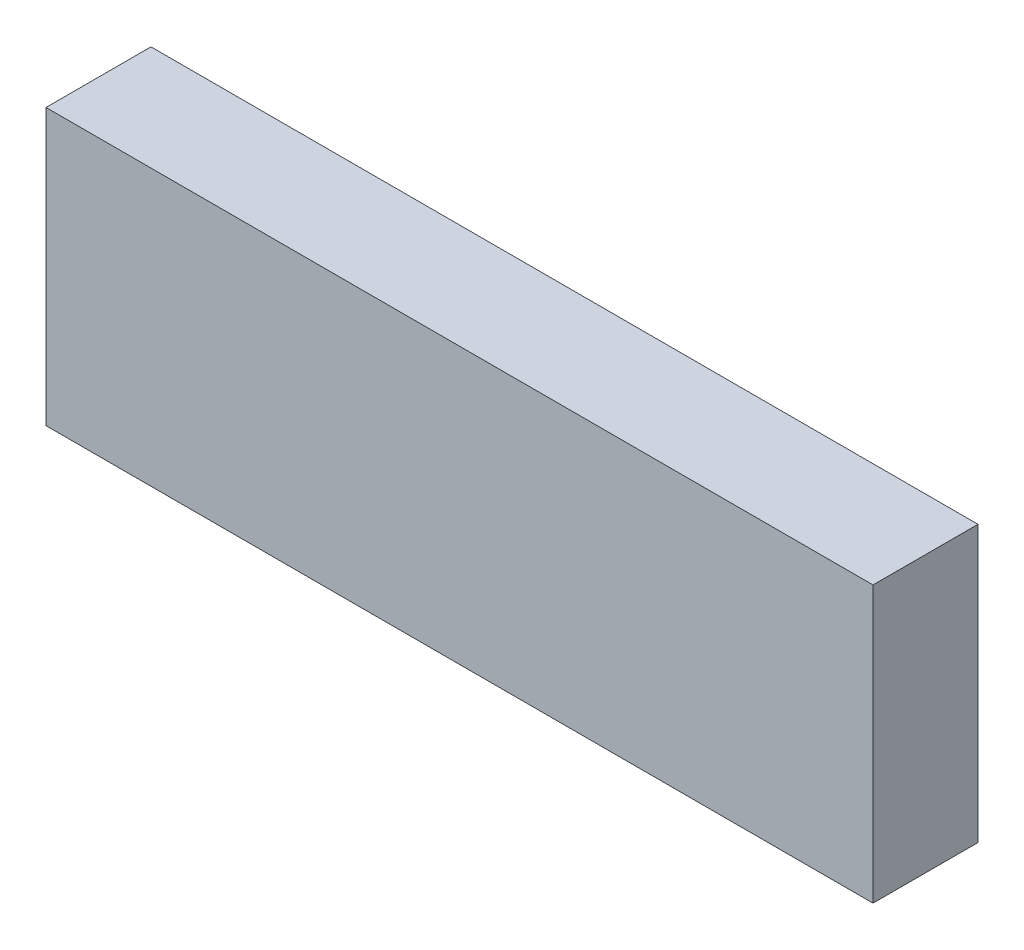
SolidWorks part; units mm, degrees
ref_plane "Front Plane" through (0, 0, 0) normal (0, 0, 1) x (1, 0, 0)
ref_plane "Top Plane" through (0, 0, 0) normal (0, 1, 0) x (1, 0, 0)
ref_plane "Right Plane" through (0, 0, 0) normal (1, 0, 0) x (0, 0, -1)
sketch "Sketch1" plane through (0, 0, 0) normal (0, 1, 0) x (1, 0, 0)
  line L1 (0, 0) -> (90.0237, 0)
  line L2 (0, 0) -> (0, 11.4284)
  line L3 (0, 11.4284) -> (90.0237, 11.4284)
  line L4 (90.0237, 0) -> (90.0237, 11.4284)
extrude "Boss-Extrude1" add sketch "Sketch1" along normal blind 30
